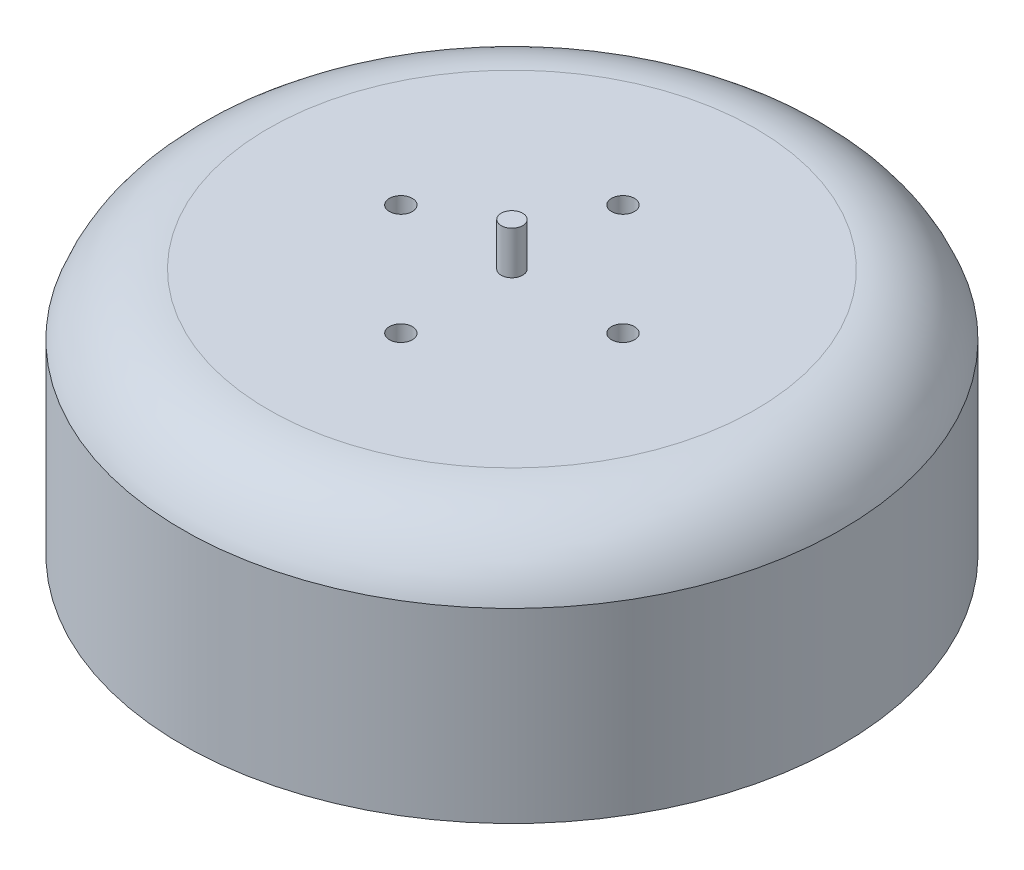
SolidWorks part; units mm, degrees
ref_plane "Front" through (0, 0, 0) normal (0, 0, 1) x (1, 0, 0)
ref_plane "Top" through (0, 0, 0) normal (0, 1, 0) x (1, 0, 0)
ref_plane "Right" through (0, 0, 0) normal (1, 0, 0) x (0, 0, -1)
sketch "Croquis1" plane through (0, 0, 0) normal (0, 0, 1) x (1, 0, 0)
  line L0 (34, 38.5) -> (0, 38.5)
  line L1 (0, 38.5) -> (0, 0)
  line L2 (0, 0) -> (46, 0)
  line L3 (46, 0) -> (46, 30)
  line L4 (0, 38.5) -> (0, 0) construction
  arc A0 (46, 30) -> (34, 38.5) centre (34, 25.7794) ccw
revolve "Revolución1" add sketch "Croquis1" angle 360 about L4
sketch "Croquis2" plane through (0, 0, 0) normal (0, -1, 0) x (1, 0, 0)
  circle A0 centre (0, 0) radius 7
extrude "Saliente-Extruir1" add sketch "Croquis2" along normal blind 3
sketch "Croquis3" plane through (0, 38.5, 0) normal (0, 1, 0) x (-1, 0, 0)
  circle A0 centre (0, 0) radius 1.5
extrude "Saliente-Extruir2" add sketch "Croquis3" along normal blind 6
hole_wizard "Diámetro de taladro Ø3.2 (3.2)1" positions "Croquis5" profile "Croquis4" hole size "Ø3.2" standard "Ansi Metric"
sketch "Croquis5" plane through (0, 38.5, 0) normal (0, 1, 0) x (1, 0, 0)
  point P0 (0, 15.5)
  point P1 (-15.5, 0)
  point P2 (15.5, 0)
  point P3 (0, -15.5)
sketch "Croquis4" plane through (0, 38.5, -15.5) normal (1, 0, 0) x (0, 0, 1)
  line L0 (0, 0) -> (0, 10)
  line L1 (0, 10) -> (1.6, 10)
  line L2 (1.6, 10) -> (1.6, 0)
  line L5 (1.6, 0) -> (0, 0)
  line L10 (0, 10) -> (-1.6, 10) construction
  line L11 (0, -6.35) -> (0, 107.95) construction
  dimension "Diámetro de taladro" = 3.2
  dimension "Profundidad de taladro" = 10
  dimension "Ángulo de perforador" = 180
hole_wizard "Diámetro de taladro Ø4.2 (4.2)1" positions "Croquis7" profile "Croquis6" hole size "Ø4.2" standard "Ansi Metric"
sketch "Croquis7" plane through (0, 0, 0) normal (0, -1, 0) x (-1, 0, 0)
  point P0 (0, -20)
  point P1 (20, 0)
  point P2 (-20, 0)
  point P3 (0, 20)
sketch "Croquis6" plane through (0, 0, 20) normal (1, 0, 0) x (0, 0, -1)
  line L0 (0, 0) -> (0, 12)
  line L1 (0, 12) -> (2.1, 12)
  line L2 (2.1, 12) -> (2.1, 0)
  line L5 (2.1, 0) -> (0, 0)
  line L10 (0, 12) -> (-2.1, 12) construction
  line L11 (0, -6.35) -> (0, 107.95) construction
  dimension "Diámetro de taladro" = 4.2
  dimension "Profundidad de taladro" = 12
  dimension "Ángulo de perforador" = 180
chamfer "Chaflán1" distance 18 angle 12.529 1 edges at (0, 0, -46)
